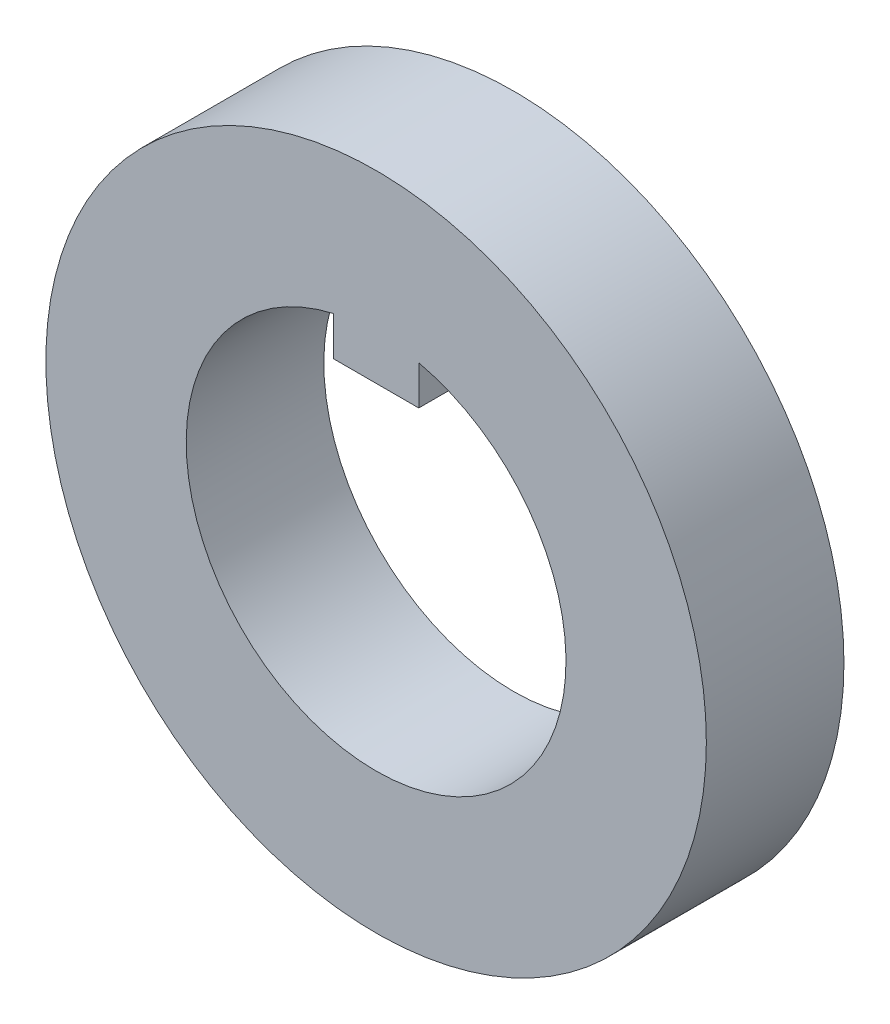
SolidWorks part; units mm, degrees
ref_plane "Front Plane" through (0, 0, 0) normal (0, 0, 1) x (1, 0, 0)
ref_plane "Top Plane" through (0, 0, 0) normal (0, 1, 0) x (1, 0, 0)
ref_plane "Right Plane" through (0, 0, 0) normal (1, 0, 0) x (0, 0, -1)
sketch "Sketch1" plane through (0, 0, 0) normal (0, 0, 1) x (1, 0, 0)
  line L0 (0, 0) -> (0, 30.48) construction
  line L2 (-3.937, 21.59) -> (3.937, 21.59)
  line L3 (-3.937, 21.59) -> (-3.937, 13.462)
  line L4 (-3.937, 13.462) -> (3.937, 13.462)
  line L5 (3.937, 21.59) -> (3.937, 13.462)
  line L6 (-3.937, 21.59) -> (3.937, 13.462) construction
  line L7 (-3.937, 13.462) -> (3.937, 21.59) construction
  circle A0 centre (0, 0) radius 30.48
  arc A1 (-3.937, 17.0781) -> (3.937, 17.0781) centre (0, 0) ccw
  point P6 (0, 17.526)
  point P11 (0, 0)
  point P12 (0, 0)
  point P13 (0, 0)
  point P14 (0, 0)
  point P15 (0, 0)
  dimension "D1" = 60.96
  dimension "D3" = 17.526
  dimension "D2" = 7.874
  dimension "D4" = 8.128
  dimension "D5" = 4.064
  dimension "D6" = 17.526
extrude "Boss-Extrude1" add sketch "Sketch1" along normal blind 12.7 contours A0 A1 L3 L2 L5 | L5 L2 L3 L4
